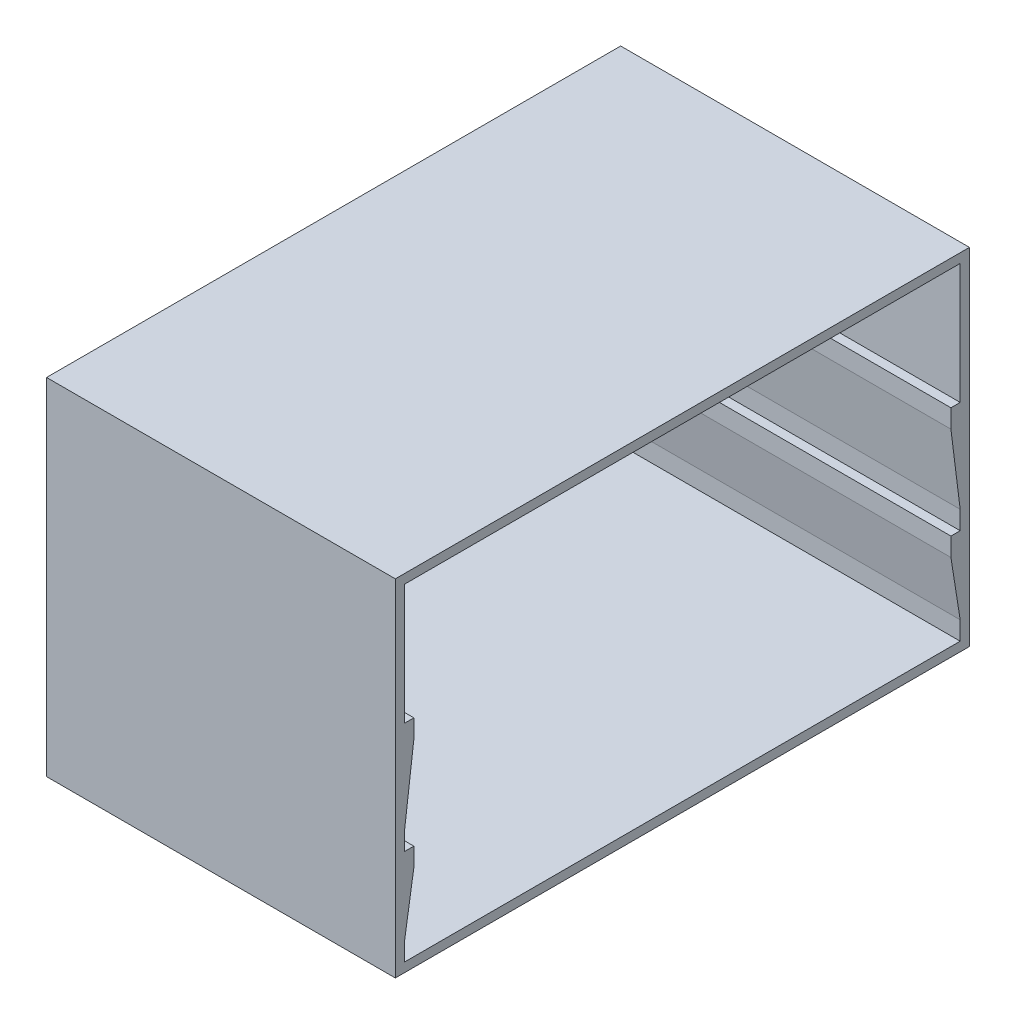
SolidWorks part; units mm, degrees
ref_plane "Front" through (0, 0, 0) normal (0, 0, 1) x (1, 0, 0)
ref_plane "Top" through (0, 0, 0) normal (0, 1, 0) x (1, 0, 0)
ref_plane "Right" through (0, 0, 0) normal (1, 0, 0) x (0, 0, -1)
sketch "Sketch1" plane through (0, 0, 0) normal (1, 0, 0) x (0, 0, -1)
  line L0 (0, 0) -> (-3, 0) construction
  line L1 (-3, 0) -> (-3, 106)
  line L2 (0, 0) -> (0, 6)
  line L3 (0, 6) -> (3, 25)
  line L4 (3, 25) -> (3, 31)
  line L5 (3, 31) -> (0, 31)
  line L6 (0, 31) -> (0, 37)
  line L7 (0, 37) -> (3, 61)
  line L9 (0, 67) -> (0, 106)
  line L10 (0, 106) -> (-3, 106) construction
  line L11 (3, 61) -> (3, 67)
  line L12 (3, 67) -> (0, 67)
  line L13 (90, 0) -> (90, 10.0674) construction
  line L14 (177, 67) -> (180, 67)
  line L15 (177, 61) -> (177, 67)
  line L16 (180, 37) -> (177, 61)
  line L17 (180, 31) -> (180, 37)
  line L18 (177, 31) -> (180, 31)
  line L19 (177, 25) -> (177, 31)
  line L20 (180, 6) -> (177, 25)
  line L21 (180, 0) -> (180, 6)
  line L22 (180, 0) -> (183, 0) construction
  line L23 (183, 0) -> (183, 106)
  line L24 (180, 106) -> (183, 106) construction
  line L25 (180, 67) -> (180, 106)
  line L26 (-3, 0) -> (-3, -3)
  line L27 (-3, -3) -> (183, -3)
  line L28 (183, -3) -> (183, 0)
  line L29 (180, 0) -> (0, 0)
  line L30 (183, 106) -> (183, 109)
  line L31 (183, 109) -> (-3, 109)
  line L32 (-3, 109) -> (-3, 106)
  line L33 (0, 106) -> (180, 106)
  dimension "D1" = 3
  dimension "D2" = 106
  dimension "D3" = 6
  dimension "D4" = 6
  dimension "D6" = 6
  dimension "D7" = 6
  dimension "D8" = 36
  dimension "D9" = 6
  dimension "D10" = 186
  dimension "D11" = 3
  dimension "D5" = 31
extrude "Boss-Extrude1" add sketch "Sketch1" along normal blind 110
sketch "Sketch2" plane through (0, 0, 0) normal (-1, 0, 0) x (0, 0, 1)
  line L1 (3, -3) -> (-183, -3)
  line L2 (3, -3) -> (3, 109)
  line L3 (3, 109) -> (-183, 109)
  line L4 (-183, -3) -> (-183, 109)
extrude "Boss-Extrude2" add sketch "Sketch2" along normal blind 3
sketch "Sketch3" plane through (0, -3, 0) normal (0, -1, 0) x (1, 0, 0)
  line L1 (-3, 3) -> (13, 3)
  line L2 (-3, 3) -> (-3, -13)
  line L3 (-3, -13) -> (13, -13)
  line L4 (13, 3) -> (13, -13)
  line L5 (110, 3) -> (94, 3)
  line L6 (110, 3) -> (110, -13)
  line L7 (110, -13) -> (94, -13)
  line L8 (94, 3) -> (94, -13)
  line L9 (110, -183) -> (94, -183)
  line L10 (110, -183) -> (110, -167)
  line L11 (110, -167) -> (94, -167)
  line L12 (94, -183) -> (94, -167)
  line L13 (-3, -183) -> (13, -183)
  line L14 (-3, -183) -> (-3, -167)
  line L15 (-3, -167) -> (13, -167)
  line L16 (13, -183) -> (13, -167)
  dimension "D1" = 16
extrude "Boss-Extrude3" add sketch "Sketch3" along normal blind 3 draft 50
equation "\"D11@Sketch1\"=\"D1@Sketch1\""
